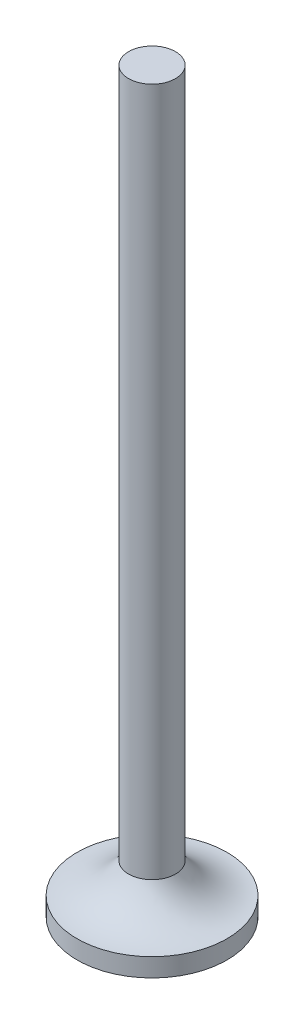
SolidWorks part; units mm, degrees
material "AISI 1020"
ref_plane "Front Plane" through (0, 0, 0) normal (0, 0, 1) x (1, 0, 0)
ref_plane "Top Plane" through (0, 0, 0) normal (0, 1, 0) x (1, 0, 0)
ref_plane "Right Plane" through (0, 0, 0) normal (1, 0, 0) x (0, 0, -1)
sketch "Sketch1" plane through (0, 0, 0) normal (0, 0, 1) x (1, 0, 0)
  line L0 (0, -31.8317) -> (0, 59.5919) construction
  line L1 (0, 0) -> (10.16, 0)
  line L2 (10.16, 0) -> (10.16, 2.5)
  line L4 (3.175, 6.6) -> (3.175, 100)
  line L5 (3.175, 100) -> (0, 100)
  line L6 (0, 100) -> (0, 0)
  arc A0 (10.16, 2.5) -> (3.175, 6.6) centre (10.16, 10.5) cw
  dimension "D5" = 8
  dimension "D1" = 10.16
  dimension "D2" = 3.175
  dimension "D3" = 2.5
  dimension "D4" = 100
revolve "Revolve1" add sketch "Sketch1" angle 360 about L0
